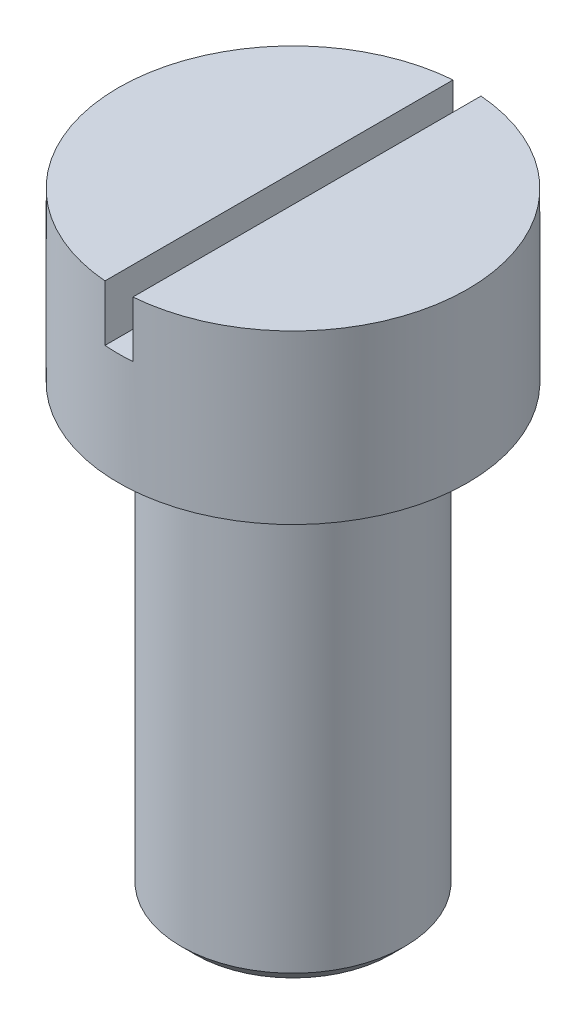
SolidWorks part; units mm, degrees
ref_plane "Front Plane" through (0, 0, 0) normal (0, 0, 1) x (1, 0, 0)
ref_plane "Top Plane" through (0, 0, 0) normal (0, 1, 0) x (1, 0, 0)
ref_plane "Right Plane" through (0, 0, 0) normal (1, 0, 0) x (0, 0, -1)
sketch "Sketch2" plane through (0, 0, 0) normal (0, 0, 1) x (1, 0, 0)
  line L0 (0, 0) -> (8, 0)
  line L1 (8, 0) -> (8, 32)
  line L2 (8, 32) -> (12.5, 32)
  line L3 (12.5, 32) -> (12.5, 44)
  line L4 (12.5, 44) -> (0, 44)
  line L5 (0, 44) -> (0, 0)
  dimension "D1" = 32
  dimension "D2" = 12
  dimension "D3" = 12.5
  dimension "D4" = 8
revolve "Revolve2" add sketch "Sketch2" angle 360 about L5
chamfer "Chamfer1" distance 1 angle 45 1 edges at (-8, 0, 0)
cosmetic thread "Cosmetic Thread1" parameters "D1"=25, "D2"=13.797
sketch "Sketch6" plane through (0, 44, 0) normal (0, 1, 0) x (1, 0, 0)
  line L1 (-1, -12.5) -> (1, -12.5)
  line L2 (-1, -12.5) -> (-1, 12.5)
  line L3 (-1, 12.5) -> (1, 12.5)
  line L4 (1, -12.5) -> (1, 12.5)
  line L5 (-1, -12.5) -> (1, 12.5) construction
  line L6 (-1, 12.5) -> (1, -12.5) construction
  circle A0 centre (0, 0) radius 12.5 construction
  point P0 (0, 0)
  dimension "D1" = 2
extrude "Cut-Extrude1" cut sketch "Sketch6" against normal blind 4
